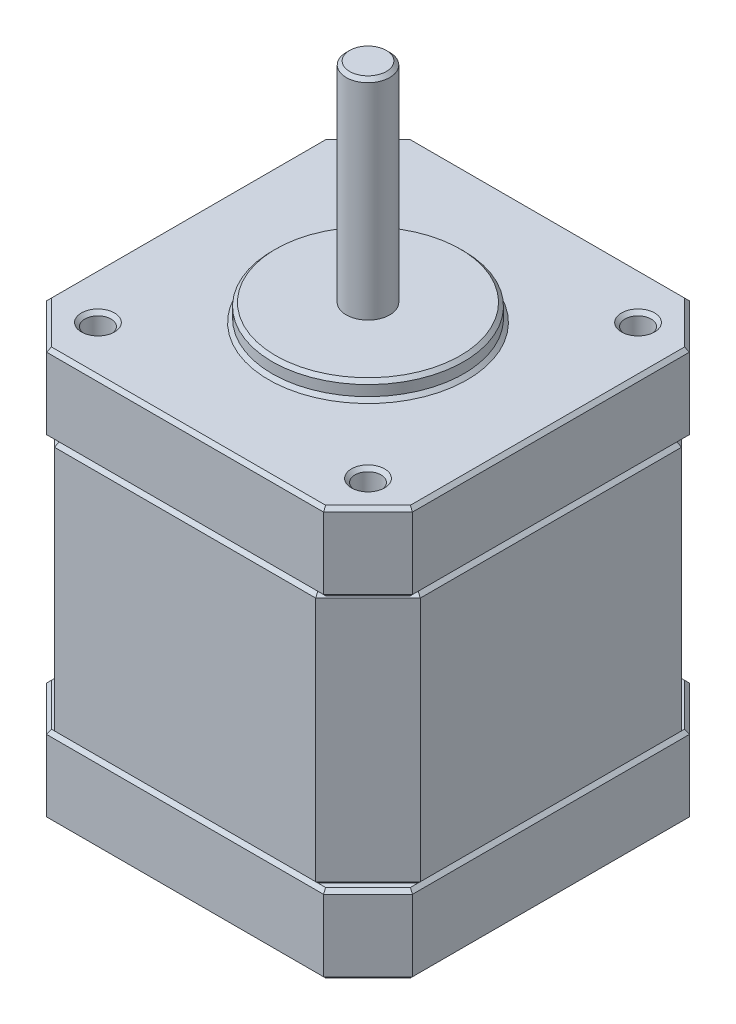
SolidWorks part; units mm, degrees
ref_plane "Front Plane" through (0, 0, 0) normal (0, 0, 1) x (1, 0, 0)
ref_plane "Top Plane" through (0, 0, 0) normal (0, 1, 0) x (1, 0, 0)
ref_plane "Right Plane" through (0, 0, 0) normal (1, 0, 0) x (0, 0, -1)
sketch "Sketch1" plane through (0, 0, 0) normal (0, 1, 0) x (1, 0, 0)
  line L1 (-21, -21) -> (21, -21)
  line L2 (-21, -21) -> (-21, 21)
  line L3 (-21, 21) -> (21, 21)
  line L4 (21, -21) -> (21, 21)
  line L5 (-21, -21) -> (21, 21) construction
  line L6 (-21, 21) -> (21, -21) construction
  point P0 (0, 0)
  dimension "D1" = 42
extrude "Boss-Extrude1" add sketch "Sketch1" along normal blind 9
chamfer "Chamfer1" distance 5.1 angle 45 4 edges at (-21, 4.5, -21) (21, 4.5, -21) (21, 4.5, 21) (-21, 4.5, 21)
chamfer "Chamfer2" distance 0.4 angle 45 16 edges at (-18.45, 0, 18.45) (0, 0, 21) (18.45, 0, 18.45) (21, 0, 0) (18.45, 0, -18.45) (0, 0, -21) (-18.45, 0, -18.45) (-21, 0, 0) (18.45, 9, -18.45) (21, 9, 0) (18.45, 9, 18.45) (0, 9, 21) (-18.45, 9, 18.45) (-21, 9, 0) (-18.45, 9, -18.45) (0, 9, -21)
sketch "Sketch3" plane through (0, 9, 0) normal (0, 1, 0) x (1, 0, 0)
  line L1 (21, 21) -> (-21, 21)
  line L2 (21, 21) -> (21, -21)
  line L3 (21, -21) -> (-21, -21)
  line L4 (-21, 21) -> (-21, -21)
  line L5 (21, 21) -> (-21, -21) construction
  line L6 (21, -21) -> (-21, 21) construction
  point P0 (0, 0)
  dimension "D1" = 42
extrude "Boss-Extrude3" add sketch "Sketch3" along normal blind 29 separate body
chamfer "Chamfer3" distance 6 angle 45 4 edges at (-21, 23.5, -21) (21, 23.5, -21) (-21, 23.5, 21) (21, 23.5, 21)
chamfer "Chamfer4" distance 0.4 angle 45 16 edges at (18, 38, -18) (21, 38, 0) (18, 38, 18) (0, 38, 21) (-18, 38, 18) (-21, 38, 0) (-18, 38, -18) (0, 38, -21) (-18, 9, 18) (0, 9, 21) (18, 9, 18) (21, 9, 0) (18, 9, -18) (0, 9, -21) (-18, 9, -18) (-21, 9, 0)
sketch "Sketch4" plane through (0, 38, 0) normal (0, 1, 0) x (1, 0, 0)
  line L1 (21, 21) -> (-21, 21)
  line L2 (21, 21) -> (21, -21)
  line L3 (21, -21) -> (-21, -21)
  line L4 (-21, 21) -> (-21, -21)
  line L5 (21, 21) -> (-21, -21) construction
  line L6 (21, -21) -> (-21, 21) construction
  point P0 (0, 0)
  dimension "D1" = 42
extrude "Boss-Extrude4" add sketch "Sketch4" along normal blind 9 separate body
chamfer "Chamfer5" distance 5.1 angle 45 4 edges at (21, 42.5, 21) (-21, 42.5, 21) (-21, 42.5, -21) (21, 42.5, -21)
sketch "Sketch5" plane through (0, 47, 0) normal (0, 1, 0) x (1, 0, 0)
  circle A0 centre (0, 0) radius 11
  dimension "D1" = 22
extrude "Boss-Extrude5" add sketch "Sketch5" along normal blind 2
sketch "Sketch7" plane through (0, 47, 0) normal (0, 1, 0) x (1, 0, 0)
  line L1 (15.5, 15.5) -> (-15.5, 15.5) construction
  line L2 (15.5, 15.5) -> (15.5, -15.5) construction
  line L3 (15.5, -15.5) -> (-15.5, -15.5) construction
  line L4 (-15.5, 15.5) -> (-15.5, -15.5) construction
  line L5 (15.5, 15.5) -> (-15.5, -15.5) construction
  line L6 (15.5, -15.5) -> (-15.5, 15.5) construction
  circle A0 centre (15.5, -15.5) radius 1.5
  circle A1 centre (-15.5, -15.5) radius 1.5
  circle A2 centre (15.5, 15.5) radius 1.5
  circle A3 centre (-15.5, 15.5) radius 1.5
  point P0 (0, 0)
  dimension "D2" = 3
  dimension "D1" = 31
extrude "Cut-Extrude1" cut sketch "Sketch7" against normal blind 5
chamfer "Chamfer6" distance 0.4 angle 45 26 edges at (-18.45, 47, 18.45) (-21, 47, 0) (-18.45, 47, -18.45) (0, 47, -21) (18.45, 47, -18.45) (21, 47, 0) (18.45, 47, 18.45) (0, 47, 21) (18.45, 38, -18.45) (0, 38, -21) (-18.45, 38, -18.45) (-21, 38, 0) (-18.45, 38, 18.45) (0, 38, 21) (18.45, 38, 18.45) (21, 38, 0) (0, 47, 11) (0, 49, 11) (15.5, 47, 17) (-15.5, 47, -14) (15.5, 47, -14) (-15.5, 47, 17) (-15.5, 42, 17) (-15.5, 42, -14) (15.5, 42, -14) (15.5, 42, 17)
sketch "Sketch6" plane through (0, 49, 0) normal (0, 1, 0) x (1, 0, 0)
  circle A0 centre (0, 0) radius 2.5
  dimension "D1" = 5
extrude "Boss-Extrude6" add sketch "Sketch6" along normal blind 24 separate body
chamfer "Chamfer7" distance 0.4 angle 45 1 edges at (0, 73, 2.5)
